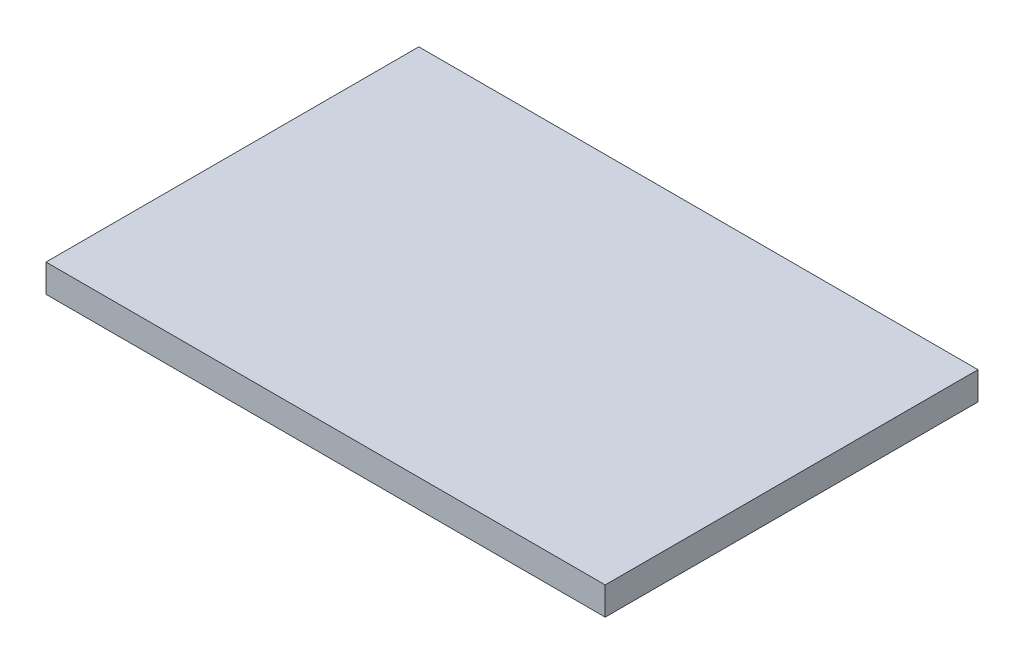
SolidWorks part; units mm, degrees
ref_plane "Front Plane" through (0, 0, 0) normal (0, 0, 1) x (1, 0, 0)
ref_plane "Top Plane" through (0, 0, 0) normal (0, 1, 0) x (1, 0, 0)
ref_plane "Right Plane" through (0, 0, 0) normal (1, 0, 0) x (0, 0, -1)
sketch "Sketch1" plane through (0, 0, 0) normal (0, 1, 0) x (1, 0, 0)
  line L1 (-30, 20) -> (30, 20)
  line L2 (-30, 20) -> (-30, -20)
  line L3 (-30, -20) -> (30, -20)
  line L4 (30, 20) -> (30, -20)
  line L5 (-30, 20) -> (30, -20) construction
  line L6 (-30, -20) -> (30, 20) construction
  point P0 (0, 0)
  dimension "D1" = 60
  dimension "D2" = 40
extrude "Boss-Extrude1" add sketch "Sketch1" along normal blind 3
